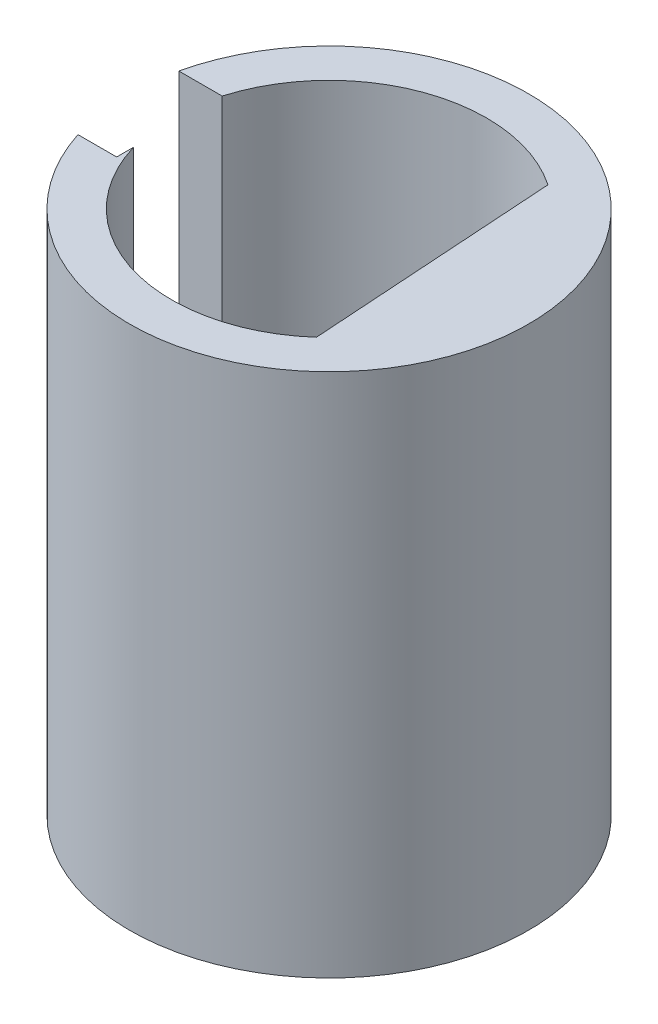
SolidWorks part; units mm, degrees
ref_plane "Front Plane" through (0, 0, 0) normal (0, 0, 1) x (1, 0, 0)
ref_plane "Top Plane" through (0, 0, 0) normal (0, 1, 0) x (1, 0, 0)
ref_plane "Right Plane" through (0, 0, 0) normal (1, 0, 0) x (0, 0, -1)
sketch "Sketch2" plane through (0, 0, 0) normal (0, 1, 0) x (1, 0, 0)
  line L0 (1.997, -2.2387) -> (1.6873, 2.4805)
  circle A0 centre (0, 0) radius 3
  circle A1 centre (0, 0) radius 3.8
  dimension "D1" = 0.8
  dimension "D2" = 6
extrude "Boss-Extrude1" add sketch "Sketch2" along normal blind 10 contours A1 A0 | L0 A0
sketch "Sketch3" plane through (0, 10, 0) normal (0, 1, 0) x (1, 0, 0)
  line L1 (-2.8791, 0.8432) -> (-4.126, 0.8432)
  line L2 (-2.8791, 0.8432) -> (-2.8791, -1.1667)
  line L3 (-2.8791, -1.1667) -> (-4.126, -1.1667)
  line L4 (-4.126, 0.8432) -> (-4.126, -1.1667)
  arc A0 (1.6873, 2.4805) -> (1.997, -2.2387) centre (0, 0) ccw construction
extrude "Cut-Extrude1" cut sketch "Sketch3" against normal blind 14
